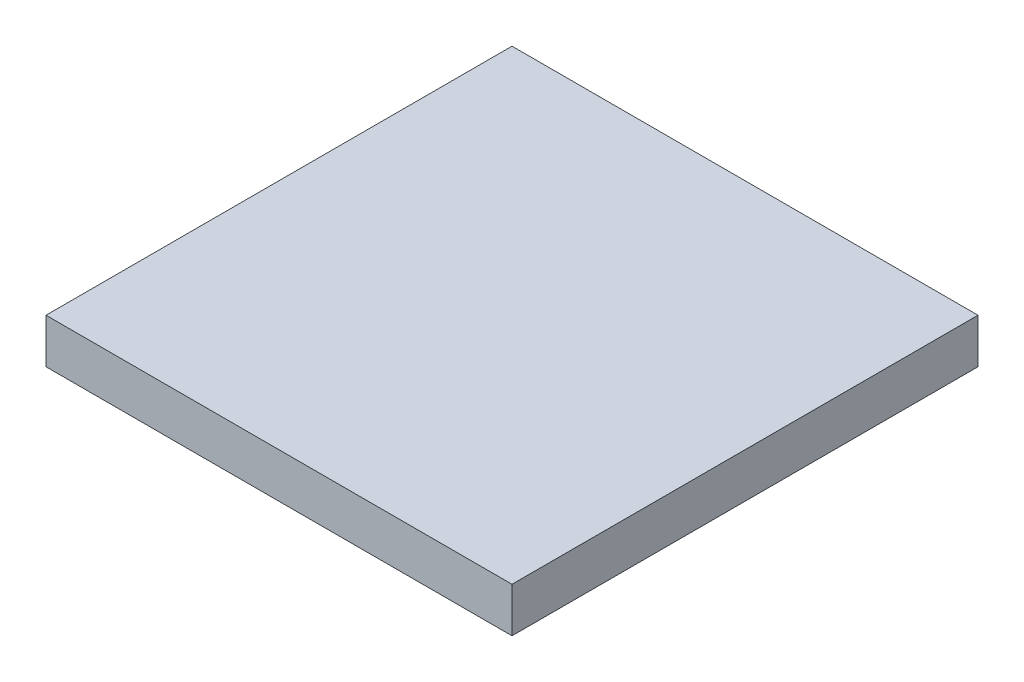
SolidWorks part; units mm, degrees
material "Pine"
ref_plane "Front Plane" through (0, 0, 0) normal (0, 0, 1) x (1, 0, 0)
ref_plane "Top Plane" through (0, 0, 0) normal (0, 1, 0) x (1, 0, 0)
ref_plane "Right Plane" through (0, 0, 0) normal (1, 0, 0) x (0, 0, -1)
sketch "Sketch1" plane through (0, 0, 0) normal (0, 1, 0) x (1, 0, 0)
  line L1 (-95.25, 95.25) -> (95.25, 95.25)
  line L2 (-95.25, 95.25) -> (-95.25, -95.25)
  line L3 (-95.25, -95.25) -> (95.25, -95.25)
  line L4 (95.25, 95.25) -> (95.25, -95.25)
  line L5 (0, -95.25) -> (0, 95.25) construction
  line L6 (-95.25, 0) -> (95.25, 0) construction
  point P0 (0, 0)
  dimension "D1" = 190.5
  dimension "D2" = 190.5
extrude "Boss-Extrude1" add sketch "Sketch1" along normal blind 18.2562
